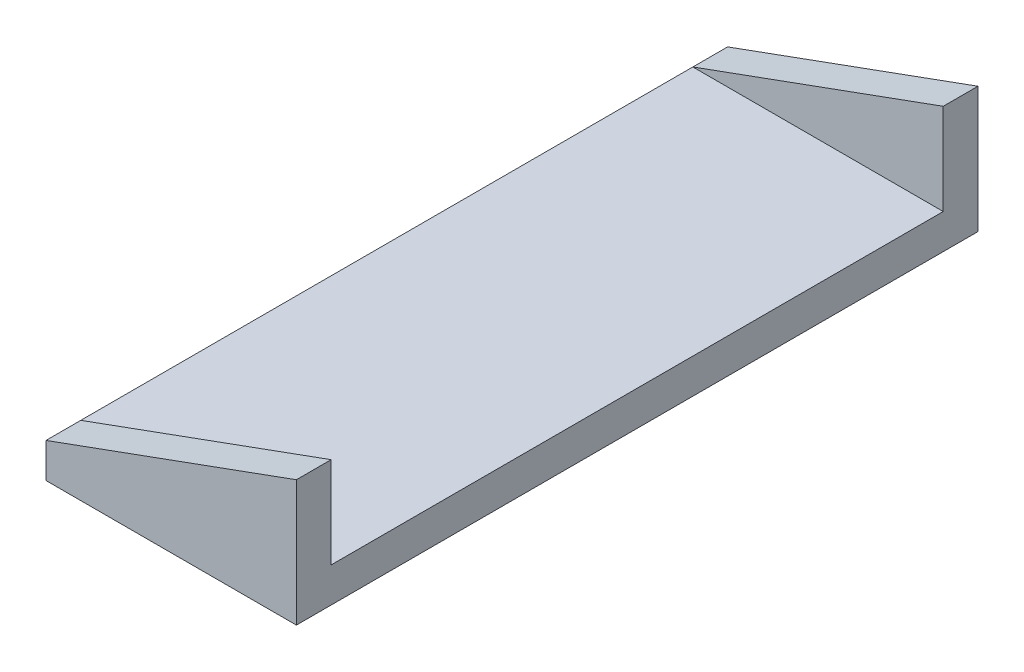
SolidWorks part; units mm, degrees
ref_plane "Front Plane" through (0, 0, 0) normal (0, 0, 1) x (1, 0, 0)
ref_plane "Top Plane" through (0, 0, 0) normal (0, 1, 0) x (1, 0, 0)
ref_plane "Right Plane" through (0, 0, 0) normal (1, 0, 0) x (0, 0, -1)
sketch "Sketch1" plane through (0, 0, 0) normal (0, 1, 0) x (1, 0, 0)
  line L1 (0, 0) -> (457.2, 0)
  line L2 (0, 0) -> (0, 1244.6)
  line L3 (0, 1244.6) -> (457.2, 1244.6)
  line L4 (457.2, 0) -> (457.2, 1244.6)
extrude "Boss-Extrude1" add sketch "Sketch1" along normal blind 63.5
sketch "Sketch4" plane through (0, 63.5, 0) normal (0, 1, 0) x (1, 0, 0)
  line L0 (0, 1244.6) -> (0, 0) construction
  line L1 (457.2, 1244.6) -> (0, 1244.6)
  line L2 (457.2, 1244.6) -> (457.2, 1181.1)
  line L3 (457.2, 1181.1) -> (0, 1181.1)
  line L4 (0, 1244.6) -> (0, 1181.1)
  line L6 (457.2, 0) -> (0, 0)
  line L7 (457.2, 0) -> (457.2, 63.5)
  line L8 (457.2, 63.5) -> (0, 63.5)
  line L9 (0, 0) -> (0, 63.5)
extrude "Boss-Extrude2" add sketch "Sketch4" along normal blind 266.7 contours L2 L1 L4 L3
sketch "Sketch6" plane through (0, 63.5, 0) normal (0, 1, 0) x (1, 0, 0)
  line L1 (0, 0) -> (304.8, 0)
  line L2 (0, 0) -> (0, 63.5)
  line L3 (0, 63.5) -> (304.8, 63.5)
  line L4 (304.8, 0) -> (304.8, 63.5)
ref_plane "Plane3" through (0, 0, -622.3) normal (0, 0, -1) x (-1, 0, 0)
sketch "Sketch10" plane through (0, 0, -1181.1) normal (0, 0, 1) x (1, 0, 0)
  line L0 (0, 63.5) -> (457.2, 229.9072)
  line L2 (457.2, 330.2) -> (457.2, 63.5) construction
  line L3 (0, 63.5) -> (0, 330.2)
  line L4 (0, 330.2) -> (457.2, 330.2)
  line L5 (457.2, 330.2) -> (457.2, 229.9072)
sketch "Sketch11" plane through (0, 0, -1181.1) normal (0, 0, 1) x (1, 0, 0)
  line L0 (0, 63.5) -> (0, 330.2)
  line L1 (0, 330.2) -> (457.2, 330.2)
  line L2 (457.2, 330.2) -> (457.2, 229.9072)
  line L6 (457.2, 229.9072) -> (0, 63.5)
mirror "Mirror7" about plane through (0, 0, -622.3) normal (0, 0, -1) of "Boss-Extrude2"
extrude "Cut-Extrude7" cut sketch "Sketch11" against normal blind 100.076
mirror "Mirror8" about plane through (0, 0, -622.3) normal (0, 0, -1) of "Cut-Extrude7"
